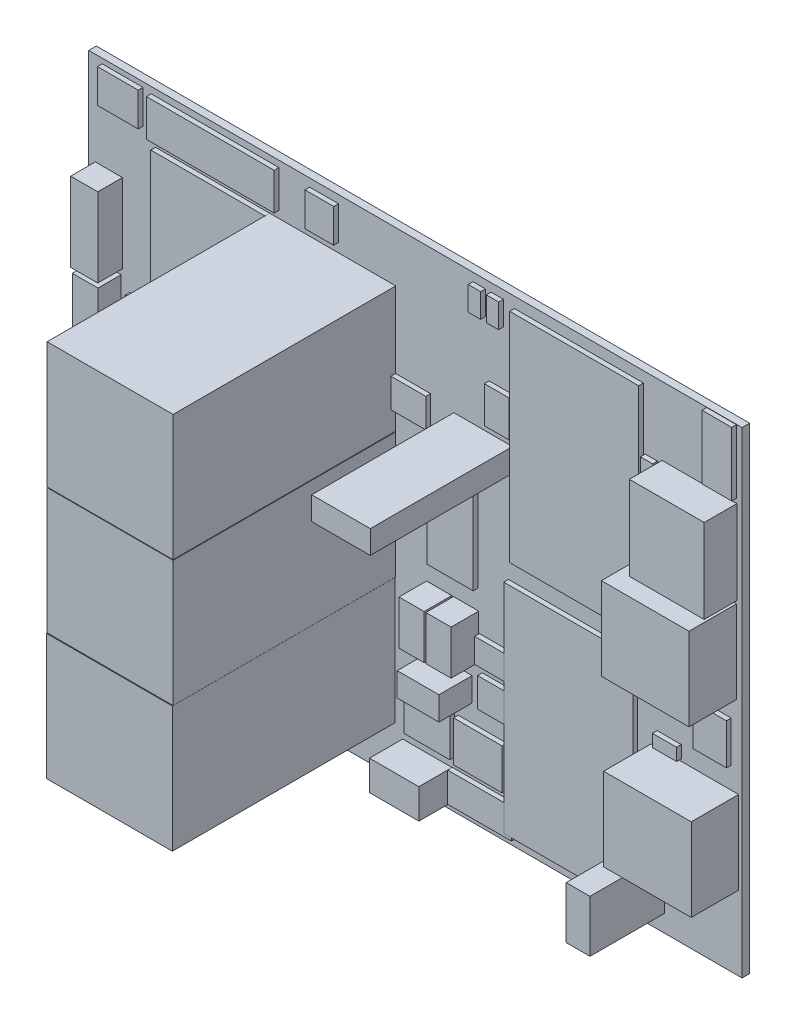
SolidWorks part; units mm, degrees
ref_plane "Plan de face" through (0, 0, 0) normal (0, 0, 1) x (1, 0, 0)
ref_plane "Plan de dessus" through (0, 0, 0) normal (0, 1, 0) x (1, 0, 0)
ref_plane "Plan de droite" through (0, 0, 0) normal (1, 0, 0) x (0, 0, -1)
sketch "Esquisse1" plane through (0, 0, 0) normal (0, 0, 1) x (1, 0, 0)
  line L0 (-2.0638, -0.1588) -> (135.87, -0.1588)
  line L1 (135.87, -0.1588) -> (135.87, 100.4762)
  line L2 (135.87, 100.4762) -> (-2.0638, 100.4762)
  line L3 (-2.0638, 100.4762) -> (-2.0638, -0.1588)
extrude "BOARD" add sketch "Esquisse1" along normal blind 1.6 separate body
ref_plane "Plan1" through (0, 0, 1.6) normal (0, 0, 1) x (1, 0, 0)
sketch "Esquisse2" plane through (0, 0, 0) normal (0, 0, 1) x (1, 0, 0)
  line L0 (109.1238, 29.3513) -> (109.1238, 26.2112)
  line L1 (109.1238, 26.2112) -> (110.9038, 26.2112)
  line L2 (110.9038, 26.2112) -> (110.9038, 29.3513)
  line L3 (110.9038, 29.3513) -> (109.1238, 29.3513)
extrude "CAP_0805-1" add sketch "Esquisse2" against normal blind 1 separate body
sketch "Esquisse3" plane through (0, 0, 0) normal (0, 0, 1) x (1, 0, 0)
  line L0 (110.9038, 22.8775) -> (110.9038, 26.0175)
  line L1 (110.9038, 26.0175) -> (109.1238, 26.0175)
  line L2 (109.1238, 26.0175) -> (109.1238, 22.8775)
  line L3 (109.1238, 22.8775) -> (110.9038, 22.8775)
extrude "CAP_0805-2" add sketch "Esquisse3" against normal blind 1 separate body
sketch "Esquisse4" plane through (0, 0, 0) normal (0, 0, 1) x (1, 0, 0)
  line L0 (94.1562, 24.0337) -> (97.2962, 24.0337)
  line L1 (97.2962, 24.0337) -> (97.2962, 25.8137)
  line L2 (97.2962, 25.8137) -> (94.1562, 25.8137)
  line L3 (94.1562, 25.8137) -> (94.1562, 24.0337)
extrude "CAP_0805-3" add sketch "Esquisse4" against normal blind 1 separate body
sketch "Esquisse5" plane through (0, 0, 0) normal (0, 0, 1) x (1, 0, 0)
  line L0 (94.7913, 37.845) -> (97.9312, 37.845)
  line L1 (97.9312, 37.845) -> (97.9312, 39.625)
  line L2 (97.9312, 39.625) -> (94.7913, 39.625)
  line L3 (94.7913, 39.625) -> (94.7913, 37.845)
extrude "CAP_0805-4" add sketch "Esquisse5" against normal blind 1 separate body
sketch "Esquisse6" plane through (0, 0, 0) normal (0, 0, 1) x (1, 0, 0)
  line L0 (68.0479, 19.7784) -> (68.0479, 15.7816)
  line L1 (68.0479, 15.7816) -> (70.0393, 15.7816)
  line L2 (70.0393, 15.7816) -> (70.0393, 19.7784)
  line L3 (70.0393, 19.7784) -> (68.0479, 19.7784)
extrude "C0805-1" add sketch "Esquisse6" against normal blind 1 separate body
sketch "Esquisse7" plane through (0, 0, 0) normal (0, 0, 1) x (1, 0, 0)
  line L0 (68.0479, 14.3809) -> (68.0479, 10.3841)
  line L1 (68.0479, 10.3841) -> (70.0393, 10.3841)
  line L2 (70.0393, 10.3841) -> (70.0393, 14.3809)
  line L3 (70.0393, 14.3809) -> (68.0479, 14.3809)
extrude "C0805-2" add sketch "Esquisse7" against normal blind 1 separate body
sketch "Esquisse8" plane through (0, 0, 1.6) normal (0, 0, 1) x (1, 0, 0)
  line L0 (36.15, 63.1475) -> (62.75, 63.1475)
  line L1 (62.75, 63.1475) -> (62.75, 36.5975)
  line L2 (62.75, 36.5975) -> (36.15, 36.5975)
  line L3 (36.15, 36.5975) -> (36.15, 63.1475)
extrude "SLPX102M200C4P3_47.000000-1" add sketch "Esquisse8" along normal blind 47 separate body
sketch "Esquisse9" plane through (0, 0, 1.6) normal (0, 0, 1) x (1, 0, 0)
  line L0 (36.15, 89.8175) -> (62.75, 89.8175)
  line L1 (62.75, 89.8175) -> (62.75, 63.2675)
  line L2 (62.75, 63.2675) -> (36.15, 63.2675)
  line L3 (36.15, 63.2675) -> (36.15, 89.8175)
extrude "SLPX102M200C4P3_47.000000-2" add sketch "Esquisse9" along normal blind 47 separate body
sketch "Esquisse10" plane through (0, 0, 1.6) normal (0, 0, 1) x (1, 0, 0)
  line L0 (62.5925, 9.8775) -> (35.9925, 9.8775)
  line L1 (35.9925, 9.8775) -> (35.9925, 36.4275)
  line L2 (35.9925, 36.4275) -> (62.5925, 36.4275)
  line L3 (62.5925, 36.4275) -> (62.5925, 9.8775)
extrude "SLPX102M200C4P3_47.000000-3" add sketch "Esquisse10" along normal blind 47 separate body
sketch "Esquisse11" plane through (0, 0, 1.6) normal (0, 0, 1) x (1, 0, 0)
  line L0 (-0.6375, 52.0425) -> (-0.6375, 62.8925)
  line L1 (-0.6375, 62.8925) -> (4.7875, 62.8925)
  line L2 (4.7875, 62.8925) -> (4.7875, 52.0425)
  line L3 (4.7875, 52.0425) -> (-0.6375, 52.0425)
extrude "TO254P490X1000X2143-3P_4.900000-1" add sketch "Esquisse11" along normal blind 4.9 separate body
sketch "Esquisse12" plane through (0, 0, 1.6) normal (0, 0, 1) x (1, 0, 0)
  line L0 (-0.955, 23.15) -> (-0.955, 34)
  line L1 (-0.955, 34) -> (4.47, 34)
  line L2 (4.47, 34) -> (4.47, 23.15)
  line L3 (4.47, 23.15) -> (-0.955, 23.15)
extrude "TO254P490X1000X2143-3P_4.900000-2" add sketch "Esquisse12" along normal blind 4.9 separate body
sketch "Esquisse13" plane through (0, 0, 0) normal (0, 0, 1) x (1, 0, 0)
  line L0 (79.5337, 11.8275) -> (85.8837, 11.8275)
  line L1 (85.8837, 11.8275) -> (85.8837, 15.4525)
  line L2 (85.8837, 15.4525) -> (79.5337, 15.4525)
  line L3 (79.5337, 15.4525) -> (79.5337, 11.8275)
extrude "SOP50P490X110-10N_1.100000-1" add sketch "Esquisse13" against normal blind 1.1 separate body
sketch "Esquisse14" plane through (0, 0, 1.6) normal (0, 0, 1) x (1, 0, 0)
  line L0 (80.4228, 29.9403) -> (80.4228, 35.0838)
  line L1 (80.4228, 35.0838) -> (88.1063, 35.0838)
  line L2 (88.1063, 35.0838) -> (88.1063, 29.9403)
  line L3 (88.1063, 29.9403) -> (80.4228, 29.9403)
extrude "AVRISP-1" add sketch "Esquisse14" along normal blind 1 separate body
sketch "Esquisse15" plane through (0, 0, 1.6) normal (0, 0, 1) x (1, 0, 0)
  line L0 (116.6438, 15.5438) -> (116.6438, 33.0337)
  line L1 (116.6438, 33.0337) -> (135.1438, 33.0337)
  line L2 (135.1438, 33.0337) -> (135.1438, 15.5438)
  line L3 (135.1438, 15.5438) -> (116.6438, 15.5438)
extrude "UJ2BH1TH_10.000000-1" add sketch "Esquisse15" along normal blind 10 separate body
sketch "Esquisse16" plane through (0, 0, 1.6) normal (0, 0, 1) x (1, 0, 0)
  line L0 (116.1675, 50.1513) -> (116.1675, 67.6412)
  line L1 (116.1675, 67.6412) -> (134.6675, 67.6412)
  line L2 (134.6675, 67.6412) -> (134.6675, 50.1513)
  line L3 (134.6675, 50.1513) -> (116.1675, 50.1513)
extrude "UJ2BH1TH_10.000000-2" add sketch "Esquisse16" along normal blind 10 separate body
sketch "Esquisse17" plane through (0, 0, 1.6) normal (0, 0, 1) x (1, 0, 0)
  line L0 (133.5663, 46.22) -> (133.5663, 37.6)
  line L1 (133.5663, 37.6) -> (126.4663, 37.6)
  line L2 (126.4663, 37.6) -> (126.4663, 46.22)
  line L3 (126.4663, 46.22) -> (133.5663, 46.22)
extrude "691210910003-1" add sketch "Esquisse17" along normal blind 1 separate body
sketch "Esquisse18" plane through (0, 0, 1.6) normal (0, 0, 1) x (1, 0, 0)
  line L0 (74.6387, 1.405) -> (64.2137, 1.405)
  line L1 (64.2137, 1.405) -> (64.2137, 7.705)
  line L2 (64.2137, 7.705) -> (74.6387, 7.705)
  line L3 (74.6387, 7.705) -> (74.6387, 1.405)
extrude "SHDR3W64P0X250_1X3_990X575X700_7.000000-1" add sketch "Esquisse18" along normal blind 7 separate body
sketch "Esquisse19" plane through (0, 0, 1.6) normal (0, 0, 1) x (1, 0, 0)
  line L0 (88.1913, 1.5275) -> (74.7313, 1.5275)
  line L1 (74.7313, 1.5275) -> (74.7313, 7.7775)
  line L2 (74.7313, 7.7775) -> (88.1913, 7.7775)
  line L3 (88.1913, 7.7775) -> (88.1913, 1.5275)
extrude "JST_B4B-XH-A_LF__SN_-1" add sketch "Esquisse19" along normal blind 1 separate body
sketch "Esquisse20" plane through (0, 0, 1.6) normal (0, 0, 1) x (1, 0, 0)
  line L0 (134.68, 100.415) -> (134.68, 86.955)
  line L1 (134.68, 86.955) -> (128.43, 86.955)
  line L2 (128.43, 86.955) -> (128.43, 100.415)
  line L3 (128.43, 100.415) -> (134.68, 100.415)
extrude "JST_B4B-XH-A_LF__SN_-2" add sketch "Esquisse20" along normal blind 1 separate body
sketch "Esquisse21" plane through (0, 0, 1.6) normal (0, 0, 1) x (1, 0, 0)
  line L0 (50.665, 91.7) -> (44.585, 91.7)
  line L1 (44.585, 91.7) -> (44.585, 98.8)
  line L2 (44.585, 98.8) -> (50.665, 98.8)
  line L3 (50.665, 98.8) -> (50.665, 91.7)
extrude "691210910002-1" add sketch "Esquisse21" along normal blind 1 separate body
sketch "Esquisse22" plane through (0, 0, 1.6) normal (0, 0, 1) x (1, 0, 0)
  line L0 (9.39, 92.335) -> (0.77, 92.335)
  line L1 (0.77, 92.335) -> (0.77, 99.435)
  line L2 (0.77, 99.435) -> (9.39, 99.435)
  line L3 (9.39, 99.435) -> (9.39, 92.335)
extrude "691210910003-2" add sketch "Esquisse22" along normal blind 1 separate body
sketch "Esquisse23" plane through (0, 0, 0) normal (0, 0, 1) x (1, 0, 0)
  line L0 (78.105, 98.8441) -> (52.6034, 98.8441)
  line L1 (52.6034, 98.8441) -> (52.6034, 93.5609)
  line L2 (52.6034, 93.5609) -> (78.105, 93.5609)
  line L3 (78.105, 93.5609) -> (78.105, 98.8441)
extrude "JTAG-20-1" add sketch "Esquisse23" against normal blind 1 separate body
sketch "Esquisse24" plane through (0, 0, 1.6) normal (0, 0, 1) x (1, 0, 0)
  line L0 (50.03, 1.2125) -> (43.95, 1.2125)
  line L1 (43.95, 1.2125) -> (43.95, 8.3125)
  line L2 (43.95, 8.3125) -> (50.03, 8.3125)
  line L3 (50.03, 8.3125) -> (50.03, 1.2125)
extrude "691210910002-2" add sketch "Esquisse24" along normal blind 1 separate body
sketch "Esquisse25" plane through (0, 0, 1.6) normal (0, 0, 1) x (1, 0, 0)
  line L0 (10.025, 0.895) -> (1.405, 0.895)
  line L1 (1.405, 0.895) -> (1.405, 7.995)
  line L2 (1.405, 7.995) -> (10.025, 7.995)
  line L3 (10.025, 7.995) -> (10.025, 0.895)
extrude "691210910003-3" add sketch "Esquisse25" along normal blind 1 separate body
sketch "Esquisse26" plane through (0, 0, 1.6) normal (0, 0, 1) x (1, 0, 0)
  line L0 (118.975, 68.29) -> (118.975, 86.03)
  line L1 (118.975, 86.03) -> (134.775, 86.03)
  line L2 (134.775, 86.03) -> (134.775, 68.29)
  line L3 (134.775, 68.29) -> (118.975, 68.29)
extrude "SS52100001_6.900000-1" add sketch "Esquisse26" along normal blind 6.9 separate body
sketch "Esquisse27" plane through (0, 0, 1.6) normal (0, 0, 1) x (1, 0, 0)
  line L0 (117.9512, 36.1125) -> (123.0312, 36.1125)
  line L1 (123.0312, 36.1125) -> (123.0312, 33.4962)
  line L2 (123.0312, 33.4962) -> (117.9512, 33.4962)
  line L3 (117.9512, 33.4962) -> (117.9512, 36.1125)
extrude "1X02-1" add sketch "Esquisse27" along normal blind 1 separate body
sketch "Esquisse28" plane through (0, 0, 1.6) normal (0, 0, 1) x (1, 0, 0)
  line L0 (118.9037, 49.4475) -> (123.9838, 49.4475)
  line L1 (123.9838, 49.4475) -> (123.9838, 46.8312)
  line L2 (123.9838, 46.8312) -> (118.9037, 46.8312)
  line L3 (118.9037, 46.8312) -> (118.9037, 49.4475)
extrude "1X02-2" add sketch "Esquisse28" along normal blind 1 separate body
sketch "Esquisse29" plane through (0, 0, 1.6) normal (0, 0, 1) x (1, 0, 0)
  line L0 (118.1862, 73.8188) -> (118.1862, 68.7387)
  line L1 (118.1862, 68.7387) -> (115.57, 68.7387)
  line L2 (115.57, 68.7387) -> (115.57, 73.8188)
  line L3 (115.57, 73.8188) -> (118.1862, 73.8188)
extrude "1X02-3" add sketch "Esquisse29" along normal blind 1 separate body
sketch "Esquisse30" plane through (0, 0, 1.6) normal (0, 0, 1) x (1, 0, 0)
  line L0 (87.63, 82.3087) -> (87.63, 74.6125)
  line L1 (87.63, 74.6125) -> (82.4738, 74.6125)
  line L2 (82.4738, 74.6125) -> (82.4738, 82.3087)
  line L3 (82.4738, 82.3087) -> (87.63, 82.3087)
extrude "2X03-1" add sketch "Esquisse30" along normal blind 1 separate body
sketch "Esquisse31" plane through (0, 0, 1.6) normal (0, 0, 1) x (1, 0, 0)
  line L0 (85.4837, 98.7425) -> (85.4837, 93.6625)
  line L1 (85.4837, 93.6625) -> (82.8675, 93.6625)
  line L2 (82.8675, 93.6625) -> (82.8675, 98.7425)
  line L3 (82.8675, 98.7425) -> (85.4837, 98.7425)
extrude "1X02-4" add sketch "Esquisse31" along normal blind 1 separate body
sketch "Esquisse32" plane through (0, 0, 1.6) normal (0, 0, 1) x (1, 0, 0)
  line L0 (81.6737, 98.7425) -> (81.6737, 93.6625)
  line L1 (81.6737, 93.6625) -> (79.0575, 93.6625)
  line L2 (79.0575, 93.6625) -> (79.0575, 98.7425)
  line L3 (79.0575, 98.7425) -> (81.6737, 98.7425)
extrude "1X02-5" add sketch "Esquisse32" along normal blind 1 separate body
sketch "Esquisse33" plane through (0, 0, 1.6) normal (0, 0, 1) x (1, 0, 0)
  line L0 (118.0275, 85.4075) -> (118.0275, 80.3275)
  line L1 (118.0275, 80.3275) -> (115.4113, 80.3275)
  line L2 (115.4113, 80.3275) -> (115.4113, 85.4075)
  line L3 (115.4113, 85.4075) -> (118.0275, 85.4075)
extrude "1X02-6" add sketch "Esquisse33" along normal blind 1 separate body
sketch "Esquisse34" plane through (0, 0, 1.6) normal (0, 0, 1) x (1, 0, 0)
  line L0 (113.792, 48.0695) -> (113.792, 2.1155)
  line L1 (113.792, 2.1155) -> (86.577, 2.1155)
  line L2 (86.577, 2.1155) -> (86.577, 48.0695)
  line L3 (86.577, 48.0695) -> (113.792, 48.0695)
extrude "IRM-10-1" add sketch "Esquisse34" along normal blind 1 separate body
sketch "Esquisse35" plane through (0, 0, 1.6) normal (0, 0, 1) x (1, 0, 0)
  line L0 (87.8205, 52.2605) -> (87.8205, 98.2145)
  line L1 (87.8205, 98.2145) -> (115.0355, 98.2145)
  line L2 (115.0355, 98.2145) -> (115.0355, 52.2605)
  line L3 (115.0355, 52.2605) -> (87.8205, 52.2605)
extrude "IRM-10-2" add sketch "Esquisse35" along normal blind 1 separate body
sketch "Esquisse36" plane through (0, 0, 1.6) normal (0, 0, 1) x (1, 0, 0)
  line L0 (74.9537, 29.7737) -> (74.9537, 39.1237)
  line L1 (74.9537, 39.1237) -> (80.2788, 39.1237)
  line L2 (80.2788, 39.1237) -> (80.2788, 29.7737)
  line L3 (80.2788, 29.7737) -> (74.9537, 29.7737)
extrude "DIP762W58P254L450H584Q4N_5.840000-1" add sketch "Esquisse36" along normal blind 5.84 separate body
sketch "Esquisse37" plane through (0, 0, 1.6) normal (0, 0, 1) x (1, 0, 0)
  line L0 (74.5887, 39.1237) -> (74.5887, 29.7737)
  line L1 (74.5887, 29.7737) -> (69.2637, 29.7737)
  line L2 (69.2637, 29.7737) -> (69.2637, 39.1238)
  line L3 (69.2637, 39.1238) -> (74.5887, 39.1237)
extrude "DIP762W58P254L450H584Q4N_5.840000-2" add sketch "Esquisse37" along normal blind 5.84 separate body
sketch "Esquisse38" plane through (0, 0, 1.6) normal (0, 0, 1) x (1, 0, 0)
  line L0 (-0.675, 64.1025) -> (-0.675, 80.7825)
  line L1 (-0.675, 80.7825) -> (5.06, 80.7825)
  line L2 (5.06, 80.7825) -> (5.06, 64.1025)
  line L3 (5.06, 64.1025) -> (-0.675, 64.1025)
extrude "TO545P521X1594X2566-3P_5.210000-1" add sketch "Esquisse38" along normal blind 5.21 separate body
sketch "Esquisse39" plane through (0, 0, 1.6) normal (0, 0, 1) x (1, 0, 0)
  line L0 (14.3775, 55.1625) -> (21.3825, 55.1625)
  line L1 (21.3825, 55.1625) -> (21.3825, 50.8825)
  line L2 (21.3825, 50.8825) -> (14.3775, 50.8825)
  line L3 (14.3775, 50.8825) -> (14.3775, 55.1625)
extrude "ZTX458_4.010000-1" add sketch "Esquisse39" along normal blind 4.01 separate body
sketch "Esquisse40" plane through (0, 0, 1.6) normal (0, 0, 1) x (1, 0, 0)
  line L0 (14.3775, 49.13) -> (21.3825, 49.13)
  line L1 (21.3825, 49.13) -> (21.3825, 44.85)
  line L2 (21.3825, 44.85) -> (14.3775, 44.85)
  line L3 (14.3775, 44.85) -> (14.3775, 49.13)
extrude "ZTX458_4.010000-2" add sketch "Esquisse40" along normal blind 4.01 separate body
sketch "Esquisse41" plane through (0, 0, 1.6) normal (0, 0, 1) x (1, 0, 0)
  line L0 (-0.805, 10.27) -> (-0.805, 21.48)
  line L1 (-0.805, 21.48) -> (4.55, 21.48)
  line L2 (4.55, 21.48) -> (4.55, 10.27)
  line L3 (4.55, 10.27) -> (-0.805, 10.27)
extrude "TO254P483X1028X1700-3P_4.830000-1" add sketch "Esquisse41" along normal blind 4.83 separate body
sketch "Esquisse42" plane through (0, 0, 0) normal (0, 0, 1) x (1, 0, 0)
  line L0 (110.9968, 14.537) -> (110.9968, 18.483)
  line L1 (110.9968, 18.483) -> (109.0307, 18.483)
  line L2 (109.0307, 18.483) -> (109.0307, 14.537)
  line L3 (109.0307, 14.537) -> (110.9968, 14.537)
extrude "R0805-1" add sketch "Esquisse42" against normal blind 1 separate body
sketch "Esquisse43" plane through (0, 0, 0) normal (0, 0, 1) x (1, 0, 0)
  line L0 (109.0307, 14.1968) -> (109.0307, 10.2508)
  line L1 (109.0307, 10.2508) -> (110.9968, 10.2508)
  line L2 (110.9968, 10.2508) -> (110.9968, 14.1968)
  line L3 (110.9968, 14.1968) -> (109.0307, 14.1968)
extrude "R0805-2" add sketch "Esquisse43" against normal blind 1 separate body
sketch "Esquisse44" plane through (0, 0, 0) normal (0, 0, 1) x (1, 0, 0)
  line L0 (118.5557, 12.2918) -> (118.5557, 8.3457)
  line L1 (118.5557, 8.3457) -> (120.5217, 8.3457)
  line L2 (120.5217, 8.3457) -> (120.5217, 12.2918)
  line L3 (120.5217, 12.2918) -> (118.5557, 12.2918)
extrude "R0805-3" add sketch "Esquisse44" against normal blind 1 separate body
sketch "Esquisse45" plane through (0, 0, 0) normal (0, 0, 1) x (1, 0, 0)
  line L0 (72.6167, 8.2855) -> (68.6707, 8.2855)
  line L1 (68.6707, 8.2855) -> (68.6707, 6.3195)
  line L2 (68.6707, 6.3195) -> (72.6167, 6.3195)
  line L3 (72.6167, 6.3195) -> (72.6167, 8.2855)
extrude "R0805-4" add sketch "Esquisse45" against normal blind 1 separate body
sketch "Esquisse46" plane through (0, 0, 0) normal (0, 0, 1) x (1, 0, 0)
  line L0 (122.7443, 8.3457) -> (122.7443, 12.2918)
  line L1 (122.7443, 12.2918) -> (120.7782, 12.2918)
  line L2 (120.7782, 12.2918) -> (120.7782, 8.3457)
  line L3 (120.7782, 8.3457) -> (122.7443, 8.3457)
extrude "R0805-5" add sketch "Esquisse46" against normal blind 1 separate body
sketch "Esquisse47" plane through (0, 0, 0) normal (0, 0, 1) x (1, 0, 0)
  line L0 (122.7443, 4.2183) -> (122.7443, 8.1643)
  line L1 (122.7443, 8.1643) -> (120.7782, 8.1643)
  line L2 (120.7782, 8.1643) -> (120.7782, 4.2183)
  line L3 (120.7782, 4.2183) -> (122.7443, 4.2183)
extrude "R0805-6" add sketch "Esquisse47" against normal blind 1 separate body
sketch "Esquisse48" plane through (0, 0, 0) normal (0, 0, 1) x (1, 0, 0)
  line L0 (106.4907, 27.8492) -> (106.4907, 23.9032)
  line L1 (106.4907, 23.9032) -> (108.4567, 23.9032)
  line L2 (108.4567, 23.9032) -> (108.4567, 27.8492)
  line L3 (108.4567, 27.8492) -> (106.4907, 27.8492)
extrude "R0805-7" add sketch "Esquisse48" against normal blind 1 separate body
sketch "Esquisse49" plane through (0, 0, 0) normal (0, 0, 1) x (1, 0, 0)
  line L0 (104.2682, 27.8492) -> (104.2682, 23.9032)
  line L1 (104.2682, 23.9032) -> (106.2343, 23.9032)
  line L2 (106.2343, 23.9032) -> (106.2343, 27.8492)
  line L3 (106.2343, 27.8492) -> (104.2682, 27.8492)
extrude "R0805-8" add sketch "Esquisse49" against normal blind 1 separate body
sketch "Esquisse50" plane through (0, 0, 0) normal (0, 0, 1) x (1, 0, 0)
  line L0 (86.428, 23.843) -> (82.482, 23.843)
  line L1 (82.482, 23.843) -> (82.482, 21.877)
  line L2 (82.482, 21.877) -> (86.428, 21.877)
  line L3 (86.428, 21.877) -> (86.428, 23.843)
extrude "R0805-9" add sketch "Esquisse50" against normal blind 1 separate body
sketch "Esquisse51" plane through (0, 0, 0) normal (0, 0, 1) x (1, 0, 0)
  line L0 (76.3282, 15.6255) -> (76.3282, 11.6795)
  line L1 (76.3282, 11.6795) -> (78.2943, 11.6795)
  line L2 (78.2943, 11.6795) -> (78.2943, 15.6255)
  line L3 (78.2943, 15.6255) -> (76.3282, 15.6255)
extrude "R0805-10" add sketch "Esquisse51" against normal blind 1 separate body
sketch "Esquisse52" plane through (0, 0, 0) normal (0, 0, 1) x (1, 0, 0)
  line L0 (70.772, 19.753) -> (70.772, 15.807)
  line L1 (70.772, 15.807) -> (72.738, 15.807)
  line L2 (72.738, 15.807) -> (72.738, 19.753)
  line L3 (72.738, 19.753) -> (70.772, 19.753)
extrude "R0805-11" add sketch "Esquisse52" against normal blind 1 separate body
sketch "Esquisse53" plane through (0, 0, 0) normal (0, 0, 1) x (1, 0, 0)
  line L0 (70.6132, 14.3555) -> (70.6132, 10.4095)
  line L1 (70.6132, 10.4095) -> (72.5793, 10.4095)
  line L2 (72.5793, 10.4095) -> (72.5793, 14.3555)
  line L3 (72.5793, 14.3555) -> (70.6132, 14.3555)
extrude "R0805-12" add sketch "Esquisse53" against normal blind 1 separate body
sketch "Esquisse54" plane through (0, 0, 0) normal (0, 0, 1) x (1, 0, 0)
  line L0 (74.3255, 45.017) -> (74.3255, 48.963)
  line L1 (74.3255, 48.963) -> (72.3595, 48.963)
  line L2 (72.3595, 48.963) -> (72.3595, 45.017)
  line L3 (72.3595, 45.017) -> (74.3255, 45.017)
extrude "R0805-13" add sketch "Esquisse54" against normal blind 1 separate body
sketch "Esquisse55" plane through (0, 0, 0) normal (0, 0, 1) x (1, 0, 0)
  line L0 (75.3383, 27.4333) -> (79.2843, 27.4333)
  line L1 (79.2843, 27.4333) -> (79.2843, 29.3993)
  line L2 (79.2843, 29.3993) -> (75.3383, 29.3993)
  line L3 (75.3383, 29.3993) -> (75.3383, 27.4333)
extrude "R0805-14" add sketch "Esquisse55" against normal blind 1 separate body
sketch "Esquisse56" plane through (0, 0, 0) normal (0, 0, 1) x (1, 0, 0)
  line L0 (68.232, 48.963) -> (68.232, 45.017)
  line L1 (68.232, 45.017) -> (70.198, 45.017)
  line L2 (70.198, 45.017) -> (70.198, 48.963)
  line L3 (70.198, 48.963) -> (68.232, 48.963)
extrude "R0805-15" add sketch "Esquisse56" against normal blind 1 separate body
sketch "Esquisse57" plane through (0, 0, 0) normal (0, 0, 1) x (1, 0, 0)
  line L0 (117.2482, 54.262) -> (121.1942, 54.262)
  line L1 (121.1942, 54.262) -> (121.1942, 56.228)
  line L2 (121.1942, 56.228) -> (117.2482, 56.228)
  line L3 (117.2482, 56.228) -> (117.2482, 54.262)
extrude "R0805-16" add sketch "Esquisse57" against normal blind 1 separate body
sketch "Esquisse58" plane through (0, 0, 0) normal (0, 0, 1) x (1, 0, 0)
  line L0 (74.3255, 49.7795) -> (74.3255, 53.7255)
  line L1 (74.3255, 53.7255) -> (72.3595, 53.7255)
  line L2 (72.3595, 53.7255) -> (72.3595, 49.7795)
  line L3 (72.3595, 49.7795) -> (74.3255, 49.7795)
extrude "R0805-17" add sketch "Esquisse58" against normal blind 1 separate body
sketch "Esquisse59" plane through (0, 0, 0) normal (0, 0, 1) x (1, 0, 0)
  line L0 (75.9733, 39.3395) -> (79.9193, 39.3395)
  line L1 (79.9193, 39.3395) -> (79.9193, 41.3055)
  line L2 (79.9193, 41.3055) -> (75.9733, 41.3055)
  line L3 (75.9733, 41.3055) -> (75.9733, 39.3395)
extrude "R0805-18" add sketch "Esquisse59" against normal blind 1 separate body
sketch "Esquisse60" plane through (0, 0, 0) normal (0, 0, 1) x (1, 0, 0)
  line L0 (68.232, 53.7255) -> (68.232, 49.7795)
  line L1 (68.232, 49.7795) -> (70.198, 49.7795)
  line L2 (70.198, 49.7795) -> (70.198, 53.7255)
  line L3 (70.198, 53.7255) -> (68.232, 53.7255)
extrude "R0805-19" add sketch "Esquisse60" against normal blind 1 separate body
sketch "Esquisse61" plane through (0, 0, 0) normal (0, 0, 1) x (1, 0, 0)
  line L0 (117.2482, 58.707) -> (121.1942, 58.707)
  line L1 (121.1942, 58.707) -> (121.1942, 60.673)
  line L2 (121.1942, 60.673) -> (117.2482, 60.673)
  line L3 (117.2482, 60.673) -> (117.2482, 58.707)
extrude "R0805-20" add sketch "Esquisse61" against normal blind 1 separate body
sketch "Esquisse62" plane through (0, 0, 0) normal (0, 0, 1) x (1, 0, 0)
  line L0 (74.2043, 41.4642) -> (70.2583, 41.4642)
  line L1 (70.2583, 41.4642) -> (70.2583, 39.4983)
  line L2 (70.2583, 39.4983) -> (74.2043, 39.4983)
  line L3 (74.2043, 39.4983) -> (74.2043, 41.4642)
extrude "R0805-21" add sketch "Esquisse62" against normal blind 1 separate body
sketch "Esquisse63" plane through (0, 0, 0) normal (0, 0, 1) x (1, 0, 0)
  line L0 (117.2482, 56.4845) -> (121.1942, 56.4845)
  line L1 (121.1942, 56.4845) -> (121.1942, 58.4505)
  line L2 (121.1942, 58.4505) -> (117.2482, 58.4505)
  line L3 (117.2482, 58.4505) -> (117.2482, 56.4845)
extrude "R0805-22" add sketch "Esquisse63" against normal blind 1 separate body
sketch "Esquisse64" plane through (0, 0, 0) normal (0, 0, 1) x (1, 0, 0)
  line L0 (72.3595, 61.3455) -> (72.3595, 57.3995)
  line L1 (72.3595, 57.3995) -> (74.3255, 57.3995)
  line L2 (74.3255, 57.3995) -> (74.3255, 61.3455)
  line L3 (74.3255, 61.3455) -> (72.3595, 61.3455)
extrude "R0805-23" add sketch "Esquisse64" against normal blind 1 separate body
sketch "Esquisse65" plane through (0, 0, 0) normal (0, 0, 1) x (1, 0, 0)
  line L0 (73.5692, 29.3993) -> (69.6232, 29.3993)
  line L1 (69.6232, 29.3993) -> (69.6232, 27.4333)
  line L2 (69.6232, 27.4333) -> (73.5692, 27.4333)
  line L3 (73.5692, 27.4333) -> (73.5692, 29.3993)
extrude "R0805-24" add sketch "Esquisse65" against normal blind 1 separate body
sketch "Esquisse66" plane through (0, 0, 0) normal (0, 0, 1) x (1, 0, 0)
  line L0 (68.232, 61.3455) -> (68.232, 57.3995)
  line L1 (68.232, 57.3995) -> (70.198, 57.3995)
  line L2 (70.198, 57.3995) -> (70.198, 61.3455)
  line L3 (70.198, 61.3455) -> (68.232, 61.3455)
extrude "R0805-25" add sketch "Esquisse66" against normal blind 1 separate body
sketch "Esquisse67" plane through (0, 0, 0) normal (0, 0, 1) x (1, 0, 0)
  line L0 (76.1695, 61.3455) -> (76.1695, 57.3995)
  line L1 (76.1695, 57.3995) -> (78.1355, 57.3995)
  line L2 (78.1355, 57.3995) -> (78.1355, 61.3455)
  line L3 (78.1355, 61.3455) -> (76.1695, 61.3455)
extrude "R0805-26" add sketch "Esquisse67" against normal blind 1 separate body
sketch "Esquisse68" plane through (0, 0, 0) normal (0, 0, 1) x (1, 0, 0)
  line L0 (80.297, 61.3455) -> (80.297, 57.3995)
  line L1 (80.297, 57.3995) -> (82.263, 57.3995)
  line L2 (82.263, 57.3995) -> (82.263, 61.3455)
  line L3 (82.263, 61.3455) -> (80.297, 61.3455)
extrude "R0805-27" add sketch "Esquisse68" against normal blind 1 separate body
sketch "Esquisse69" plane through (0, 0, 0) normal (0, 0, 1) x (1, 0, 0)
  line L0 (68.867, 67.5367) -> (68.867, 63.5907)
  line L1 (68.867, 63.5907) -> (70.833, 63.5907)
  line L2 (70.833, 63.5907) -> (70.833, 67.5367)
  line L3 (70.833, 67.5367) -> (68.867, 67.5367)
extrude "R0805-28" add sketch "Esquisse69" against normal blind 1 separate body
sketch "Esquisse70" plane through (0, 0, 0) normal (0, 0, 1) x (1, 0, 0)
  line L0 (78.1355, 45.017) -> (78.1355, 48.963)
  line L1 (78.1355, 48.963) -> (76.1695, 48.963)
  line L2 (76.1695, 48.963) -> (76.1695, 45.017)
  line L3 (76.1695, 45.017) -> (78.1355, 45.017)
extrude "R0805-29" add sketch "Esquisse70" against normal blind 1 separate body
sketch "Esquisse71" plane through (0, 0, 0) normal (0, 0, 1) x (1, 0, 0)
  line L0 (80.297, 48.963) -> (80.297, 45.017)
  line L1 (80.297, 45.017) -> (82.263, 45.017)
  line L2 (82.263, 45.017) -> (82.263, 48.963)
  line L3 (82.263, 48.963) -> (80.297, 48.963)
extrude "R0805-30" add sketch "Esquisse71" against normal blind 1 separate body
sketch "Esquisse72" plane through (0, 0, 0) normal (0, 0, 1) x (1, 0, 0)
  line L0 (82.263, 49.7795) -> (82.263, 53.7255)
  line L1 (82.263, 53.7255) -> (80.297, 53.7255)
  line L2 (80.297, 53.7255) -> (80.297, 49.7795)
  line L3 (80.297, 49.7795) -> (82.263, 49.7795)
extrude "R0805-31" add sketch "Esquisse72" against normal blind 1 separate body
sketch "Esquisse73" plane through (0, 0, 0) normal (0, 0, 1) x (1, 0, 0)
  line L0 (76.1695, 53.7255) -> (76.1695, 49.7795)
  line L1 (76.1695, 49.7795) -> (78.1355, 49.7795)
  line L2 (78.1355, 49.7795) -> (78.1355, 53.7255)
  line L3 (78.1355, 53.7255) -> (76.1695, 53.7255)
extrude "R0805-32" add sketch "Esquisse73" against normal blind 1 separate body
sketch "Esquisse74" plane through (0, 0, 0) normal (0, 0, 1) x (1, 0, 0)
  line L0 (68.6359, 87.2191) -> (68.6359, 91.2159)
  line L1 (68.6359, 91.2159) -> (66.6445, 91.2159)
  line L2 (66.6445, 91.2159) -> (66.6445, 87.2191)
  line L3 (66.6445, 87.2191) -> (68.6359, 87.2191)
extrude "M0805-1" add sketch "Esquisse74" against normal blind 1 separate body
sketch "Esquisse75" plane through (0, 0, 0) normal (0, 0, 1) x (1, 0, 0)
  line L0 (70.8584, 87.2191) -> (70.8584, 91.2159)
  line L1 (70.8584, 91.2159) -> (68.867, 91.2159)
  line L2 (68.867, 91.2159) -> (68.867, 87.2191)
  line L3 (68.867, 87.2191) -> (70.8584, 87.2191)
extrude "M0805-2" add sketch "Esquisse75" against normal blind 1 separate body
sketch "Esquisse76" plane through (0, 0, 0) normal (0, 0, 1) x (1, 0, 0)
  line L0 (73.0809, 87.2191) -> (73.0809, 91.2159)
  line L1 (73.0809, 91.2159) -> (71.0895, 91.2159)
  line L2 (71.0895, 91.2159) -> (71.0895, 87.2191)
  line L3 (71.0895, 87.2191) -> (73.0809, 87.2191)
extrude "M0805-3" add sketch "Esquisse76" against normal blind 1 separate body
sketch "Esquisse77" plane through (0, 0, 0) normal (0, 0, 1) x (1, 0, 0)
  line L0 (80.5891, 91.2159) -> (80.5891, 87.2191)
  line L1 (80.5891, 87.2191) -> (82.5805, 87.2191)
  line L2 (82.5805, 87.2191) -> (82.5805, 91.2159)
  line L3 (82.5805, 91.2159) -> (80.5891, 91.2159)
extrude "M0805-4" add sketch "Esquisse77" against normal blind 1 separate body
sketch "Esquisse78" plane through (0, 0, 0) normal (0, 0, 1) x (1, 0, 0)
  line L0 (82.8116, 91.2159) -> (82.8116, 87.2191)
  line L1 (82.8116, 87.2191) -> (84.803, 87.2191)
  line L2 (84.803, 87.2191) -> (84.803, 91.2159)
  line L3 (84.803, 91.2159) -> (82.8116, 91.2159)
extrude "M0805-5" add sketch "Esquisse78" against normal blind 1 separate body
sketch "Esquisse79" plane through (0, 0, 0) normal (0, 0, 1) x (1, 0, 0)
  line L0 (78.3666, 91.2159) -> (78.3666, 87.2191)
  line L1 (78.3666, 87.2191) -> (80.358, 87.2191)
  line L2 (80.358, 87.2191) -> (80.358, 91.2159)
  line L3 (80.358, 91.2159) -> (78.3666, 91.2159)
extrude "M0805-6" add sketch "Esquisse79" against normal blind 1 separate body
sketch "Esquisse80" plane through (0, 0, 0) normal (0, 0, 1) x (1, 0, 0)
  line L0 (73.4454, 91.2159) -> (73.4454, 87.2191)
  line L1 (73.4454, 87.2191) -> (75.4368, 87.2191)
  line L2 (75.4368, 87.2191) -> (75.4368, 91.2159)
  line L3 (75.4368, 91.2159) -> (73.4454, 91.2159)
extrude "M0805-7" add sketch "Esquisse80" against normal blind 1 separate body
sketch "Esquisse81" plane through (0, 0, 0) normal (0, 0, 1) x (1, 0, 0)
  line L0 (77.8434, 87.2191) -> (77.8434, 91.2159)
  line L1 (77.8434, 91.2159) -> (75.852, 91.2159)
  line L2 (75.852, 91.2159) -> (75.852, 87.2191)
  line L3 (75.852, 87.2191) -> (77.8434, 87.2191)
extrude "M0805-8" add sketch "Esquisse81" against normal blind 1 separate body
sketch "Esquisse82" plane through (0, 0, 0) normal (0, 0, 1) x (1, 0, 0)
  line L0 (75.1916, 67.5622) -> (75.1916, 63.5653)
  line L1 (75.1916, 63.5653) -> (77.183, 63.5654)
  line L2 (77.183, 63.5654) -> (77.183, 67.5622)
  line L3 (77.183, 67.5622) -> (75.1916, 67.5622)
extrude "M0805-9" add sketch "Esquisse82" against normal blind 1 separate body
sketch "Esquisse83" plane through (0, 0, 0) normal (0, 0, 1) x (1, 0, 0)
  line L0 (77.2554, 67.5622) -> (77.2554, 63.5653)
  line L1 (77.2554, 63.5653) -> (79.2468, 63.5654)
  line L2 (79.2468, 63.5654) -> (79.2468, 67.5622)
  line L3 (79.2468, 67.5622) -> (77.2554, 67.5622)
extrude "M0805-10" add sketch "Esquisse83" against normal blind 1 separate body
sketch "Esquisse84" plane through (0, 0, 0) normal (0, 0, 1) x (1, 0, 0)
  line L0 (71.0641, 67.5622) -> (71.0641, 63.5653)
  line L1 (71.0641, 63.5653) -> (73.0555, 63.5654)
  line L2 (73.0555, 63.5654) -> (73.0555, 67.5622)
  line L3 (73.0555, 67.5622) -> (71.0641, 67.5622)
extrude "M0805-11" add sketch "Esquisse84" against normal blind 1 separate body
sketch "Esquisse85" plane through (0, 0, 0) normal (0, 0, 1) x (1, 0, 0)
  line L0 (73.1279, 67.5622) -> (73.1279, 63.5653)
  line L1 (73.1279, 63.5653) -> (75.1193, 63.5654)
  line L2 (75.1193, 63.5654) -> (75.1193, 67.5622)
  line L3 (75.1193, 67.5622) -> (73.1279, 67.5622)
extrude "M0805-12" add sketch "Esquisse85" against normal blind 1 separate body
sketch "Esquisse86" plane through (0, 0, 1.6) normal (0, 0, 1) x (1, 0, 0)
  line L0 (11.1125, 99.125) -> (38.0875, 99.125)
  line L1 (38.0875, 99.125) -> (38.0875, 91.2988)
  line L2 (38.0875, 91.2988) -> (11.1125, 91.2988)
  line L3 (11.1125, 91.2988) -> (11.1125, 99.125)
extrude "RS05_69-70-1" add sketch "Esquisse86" along normal blind 1 separate body
sketch "Esquisse87" plane through (0, 0, 1.6) normal (0, 0, 1) x (1, 0, 0)
  line L0 (11.7475, 8.6375) -> (38.7225, 8.6375)
  line L1 (38.7225, 8.6375) -> (38.7225, 0.8113)
  line L2 (38.7225, 0.8113) -> (11.7475, 0.8113)
  line L3 (11.7475, 0.8113) -> (11.7475, 8.6375)
extrude "RS05_69-70-2" add sketch "Esquisse87" along normal blind 1 separate body
sketch "Esquisse88" plane through (0, 0, 0) normal (0, 0, 1) x (1, 0, 0)
  line L0 (8.636, 68.2625) -> (8.636, 76.1365)
  line L1 (8.636, 76.1365) -> (6.604, 76.1365)
  line L2 (6.604, 76.1365) -> (6.604, 68.2625)
  line L3 (6.604, 68.2625) -> (8.636, 68.2625)
extrude "0204_7-1" add sketch "Esquisse88" against normal blind 1 separate body
sketch "Esquisse89" plane through (0, 0, 1.6) normal (0, 0, 1) x (1, 0, 0)
  line L0 (6.604, 52.705) -> (6.604, 60.579)
  line L1 (6.604, 60.579) -> (8.636, 60.579)
  line L2 (8.636, 60.579) -> (8.636, 52.705)
  line L3 (8.636, 52.705) -> (6.604, 52.705)
extrude "0204_7-2" add sketch "Esquisse89" along normal blind 1 separate body
sketch "Esquisse90" plane through (0, 0, 1.6) normal (0, 0, 1) x (1, 0, 0)
  line L0 (8.636, 19.3675) -> (8.636, 11.4935)
  line L1 (8.636, 11.4935) -> (6.604, 11.4935)
  line L2 (6.604, 11.4935) -> (6.604, 19.3675)
  line L3 (6.604, 19.3675) -> (8.636, 19.3675)
extrude "0204_7-3" add sketch "Esquisse90" along normal blind 1 separate body
sketch "Esquisse91" plane through (0, 0, 1.6) normal (0, 0, 1) x (1, 0, 0)
  line L0 (25.4, 50.8635) -> (33.274, 50.8635)
  line L1 (33.274, 50.8635) -> (33.274, 48.8315)
  line L2 (33.274, 48.8315) -> (25.4, 48.8315)
  line L3 (25.4, 48.8315) -> (25.4, 50.8635)
extrude "0204_7-4" add sketch "Esquisse91" along normal blind 1 separate body
sketch "Esquisse92" plane through (0, 0, 1.6) normal (0, 0, 1) x (1, 0, 0)
  line L0 (8.636, 40.64) -> (8.636, 32.766)
  line L1 (8.636, 32.766) -> (6.604, 32.766)
  line L2 (6.604, 32.766) -> (6.604, 40.64)
  line L3 (6.604, 40.64) -> (8.636, 40.64)
extrude "0204_7-5" add sketch "Esquisse92" along normal blind 1 separate body
sketch "Esquisse93" plane through (0, 0, 1.6) normal (0, 0, 1) x (1, 0, 0)
  line L0 (25.4, 53.4035) -> (33.274, 53.4035)
  line L1 (33.274, 53.4035) -> (33.274, 51.3715)
  line L2 (33.274, 51.3715) -> (25.4, 51.3715)
  line L3 (25.4, 51.3715) -> (25.4, 53.4035)
extrude "0204_7-6" add sketch "Esquisse93" along normal blind 1 separate body
sketch "Esquisse94" plane through (0, 0, 1.6) normal (0, 0, 1) x (1, 0, 0)
  line L0 (81.0375, 28.222) -> (88.66, 28.222)
  line L1 (88.66, 28.222) -> (88.66, 22.0825)
  line L2 (88.66, 22.0825) -> (81.0375, 22.0825)
  line L3 (81.0375, 22.0825) -> (81.0375, 28.222)
extrude "1825910-6-1" add sketch "Esquisse94" along normal blind 1 separate body
sketch "Esquisse95" plane through (0, 0, 1.6) normal (0, 0, 1) x (1, 0, 0)
  line L0 (70.0925, 67.663) -> (62.47, 67.663)
  line L1 (62.47, 67.663) -> (62.47, 73.8025)
  line L2 (62.47, 73.8025) -> (70.0925, 73.8025)
  line L3 (70.0925, 73.8025) -> (70.0925, 67.663)
extrude "1825910-6-2" add sketch "Esquisse95" along normal blind 1 separate body
sketch "Esquisse96" plane through (0, 0, 0) normal (0, 0, 1) x (1, 0, 0)
  line L0 (119.3113, 19.5645) -> (119.3113, 30.1999)
  line L1 (119.3113, 30.1999) -> (111.452, 30.1999)
  line L2 (111.452, 30.1999) -> (111.452, 19.5645)
  line L3 (111.452, 19.5645) -> (119.3113, 19.5645)
extrude "SSOP28DB-1" add sketch "Esquisse96" against normal blind 1 separate body
sketch "Esquisse97" plane through (0, 0, 1.6) normal (0, 0, 1) x (1, 0, 0)
  line L0 (114.4887, 14.4662) -> (119.5088, 14.4662)
  line L1 (119.5088, 14.4662) -> (119.5088, 3.4912)
  line L2 (119.5088, 3.4912) -> (114.4887, 3.4912)
  line L3 (114.4887, 3.4912) -> (114.4887, 14.4662)
extrude "ON_SEMI_LM317BTG_0_15.750000-1" add sketch "Esquisse97" along normal blind 15.75 separate body
sketch "Esquisse98" plane through (0, 0, 0) normal (0, 0, 1) x (1, 0, 0)
  line L0 (89.0213, 15.3587) -> (98.6213, 15.3587)
  line L1 (98.6213, 15.3587) -> (98.6213, 23.0587)
  line L2 (98.6213, 23.0587) -> (89.0213, 23.0587)
  line L3 (89.0213, 23.0587) -> (89.0213, 15.3587)
extrude "NATIONAL_SEMICONDUCTOR_LM1117IMPX-3_3-NOPB_2-1" add sketch "Esquisse98" against normal blind 1 separate body
sketch "Esquisse99" plane through (0, 0, 0) normal (0, 0, 1) x (1, 0, 0)
  line L0 (91.2438, 65.8413) -> (100.8438, 65.8413)
  line L1 (100.8438, 65.8413) -> (100.8438, 73.5412)
  line L2 (100.8438, 73.5412) -> (91.2438, 73.5412)
  line L3 (91.2438, 73.5412) -> (91.2438, 65.8413)
extrude "NATIONAL_SEMICONDUCTOR_LM1117IMPX-3_3-NOPB_2-2" add sketch "Esquisse99" against normal blind 1 separate body
sketch "Esquisse100" plane through (0, 0, 0) normal (0, 0, 1) x (1, 0, 0)
  line L0 (101.8612, 26.7263) -> (101.8612, 37.7263)
  line L1 (101.8612, 37.7263) -> (90.8612, 37.7263)
  line L2 (90.8612, 37.7263) -> (90.8612, 26.7263)
  line L3 (90.8612, 26.7263) -> (101.8612, 26.7263)
extrude "QFP80P900X900X120-32N-1" add sketch "Esquisse100" against normal blind 1 separate body
sketch "Esquisse101" plane through (0, 0, 1.6) normal (0, 0, 1) x (1, 0, 0)
  line L0 (65.4763, 20.6) -> (75.1762, 20.6)
  line L1 (75.1762, 20.6) -> (75.1762, 9.89)
  line L2 (75.1762, 9.89) -> (65.4763, 9.89)
  line L3 (65.4763, 9.89) -> (65.4763, 20.6)
extrude "TEXAS_INSTRUMENTS_TLC2262CP_0-1" add sketch "Esquisse101" along normal blind 1 separate body
sketch "Esquisse102" plane through (0, 0, 1.6) normal (0, 0, 1) x (1, 0, 0)
  line L0 (75.9651, 9.3599) -> (75.9651, 17.9451)
  line L1 (75.9651, 17.9451) -> (86.2013, 17.9451)
  line L2 (86.2013, 17.9451) -> (86.2013, 9.3599)
  line L3 (86.2013, 9.3599) -> (75.9651, 9.3599)
extrude "DIP254P762X533-8-1" add sketch "Esquisse102" along normal blind 1 separate body
sketch "Esquisse103" plane through (0, 0, 1.6) normal (0, 0, 1) x (1, 0, 0)
  line L0 (70.3975, 63.44) -> (80.0975, 63.44)
  line L1 (80.0975, 63.44) -> (80.0975, 43.24)
  line L2 (80.0975, 43.24) -> (70.3975, 43.24)
  line L3 (70.3975, 43.24) -> (70.3975, 63.44)
extrude "TEXAS_INSTRUMENTS_TLC2264CN_0-1" add sketch "Esquisse103" along normal blind 1 separate body
sketch "Esquisse104" plane through (0, 0, 1.6) normal (0, 0, 1) x (1, 0, 0)
  line L0 (12.03, 55.6075) -> (12.03, 89.8075)
  line L1 (12.03, 89.8075) -> (36.13, 89.8075)
  line L2 (36.13, 89.8075) -> (36.13, 55.6075)
  line L3 (36.13, 55.6075) -> (12.03, 55.6075)
extrude "SC-10-30J-1" add sketch "Esquisse104" along normal blind 1 separate body
sketch "Esquisse105" plane through (0, 0, 1.6) normal (0, 0, 1) x (1, 0, 0)
  line L0 (35.2775, 44.0875) -> (35.2775, 9.8875)
  line L1 (35.2775, 9.8875) -> (11.1775, 9.8875)
  line L2 (11.1775, 9.8875) -> (11.1775, 44.0875)
  line L3 (11.1775, 44.0875) -> (35.2775, 44.0875)
extrude "SC-10-30J-2" add sketch "Esquisse105" along normal blind 1 separate body
sketch "Esquisse106" plane through (0, 0, 0) normal (0, 0, 1) x (1, 0, 0)
  line L0 (79.9812, 72.1725) -> (79.9812, 83.6325)
  line L1 (79.9812, 83.6325) -> (69.5613, 83.6325)
  line L2 (69.5613, 83.6325) -> (69.5613, 72.1725)
  line L3 (69.5613, 72.1725) -> (79.9812, 72.1725)
extrude "QFP50P900X900X160-48N-1" add sketch "Esquisse106" against normal blind 1 separate body
sketch "Esquisse107" plane through (0, 0, 1.6) normal (0, 0, 1) x (1, 0, 0)
  line L0 (75.0225, 72.7772) -> (87.3985, 72.7772)
  line L1 (87.3985, 72.7772) -> (87.3985, 67.8753)
  line L2 (87.3985, 67.8753) -> (75.0225, 67.8753)
  line L3 (75.0225, 67.8753) -> (75.0225, 72.7772)
extrude "FOX_ELECTRONICS_FOXSLF-080-20_0_30.020000-1" add sketch "Esquisse107" along normal blind 30.02 separate body
sketch "Esquisse108" plane through (0, 0, 1.6) normal (0, 0, 1) x (1, 0, 0)
  line L0 (70.0502, 26.63) -> (78.8762, 26.63)
  line L1 (78.8762, 26.63) -> (78.8762, 21.63)
  line L2 (78.8762, 21.63) -> (70.0502, 21.63)
  line L3 (70.0502, 21.63) -> (70.0502, 26.63)
extrude "CSTLS16M0X53ZA0_7.000000-1" add sketch "Esquisse108" along normal blind 7 separate body
